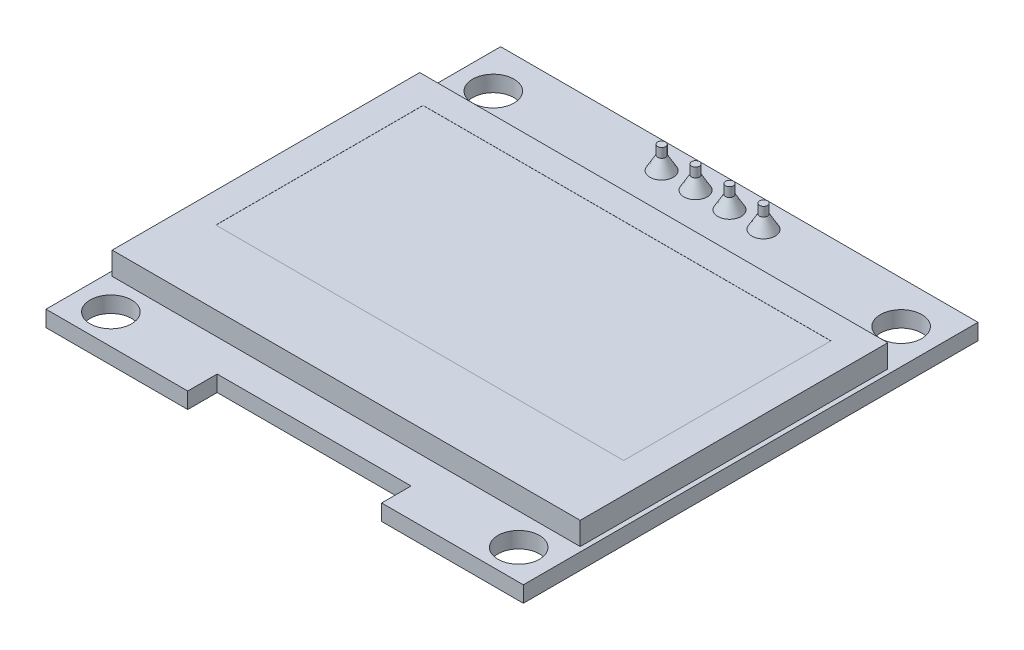
SolidWorks part; units mm, degrees
ref_plane "Ebene vorne" through (0, 0, 0) normal (0, 0, 1) x (1, 0, 0)
ref_plane "Ebene oben" through (0, 0, 0) normal (0, 1, 0) x (1, 0, 0)
ref_plane "Ebene rechts" through (0, 0, 0) normal (1, 0, 0) x (0, 0, -1)
sketch "Skizze1" plane through (0, 0, 0) normal (0, 1, 0) x (1, 0, 0)
  line L1 (-17.85, -17) -> (17.85, -17)
  line L2 (-17.85, -17) -> (-17.85, 17)
  line L3 (-17.85, 17) -> (17.85, 17)
  line L4 (17.85, -17) -> (17.85, 17)
  line L5 (-17.85, -17) -> (17.85, 17) construction
  line L6 (-17.85, 17) -> (17.85, -17) construction
  point P0 (0, 0)
  dimension "D1" = 35.7
  dimension "D2" = 34
extrude "Aufsatz-Linear austragen1" add sketch "Skizze1" along normal blind 1.2
sketch "Skizze2" plane through (0, 1.2, 0) normal (0, 1, 0) x (1, 0, 0)
  line L0 (0, 17) -> (0, -17) construction
  line L1 (17.85, 17) -> (-17.85, 17) construction
  line L2 (-17.85, -17) -> (17.85, -17) construction
  circle A0 centre (-15.25, 13.85) radius 1.55
  circle A1 centre (15.25, 13.85) radius 1.55
  circle A2 centre (15.25, -14.75) radius 1.55
  circle A3 centre (-15.25, -14.75) radius 1.55
  dimension "D4" = 3.1
  dimension "D1" = 28.6
  dimension "D2" = 30.5
  dimension "D3" = 3.15
extrude "Schnitt-Linear austragen1" cut sketch "Skizze2" against normal through all
sketch "Skizze3" plane through (0, 1.2, 0) normal (0, 1, 0) x (1, 0, 0)
  line L0 (0, 0) -> (0, 10.6) construction
  line L1 (-17.5, 10.6) -> (17.5, 10.6)
  line L2 (-17.5, 10.6) -> (-17.5, -12.4)
  line L3 (-17.5, -12.4) -> (17.5, -12.4)
  line L4 (17.5, 10.6) -> (17.5, -12.4)
  line L5 (17.85, 17) -> (-17.85, 17) construction
  dimension "D1" = 35
  dimension "D2" = 23
  dimension "D3" = 6.4
extrude "Aufsatz-Linear austragen2" add sketch "Skizze3" along normal blind 1.7
sketch "Skizze4" plane through (0, 2.9, 0) normal (0, 1, 0) x (1, 0, 0)
  line L0 (0, 0) -> (0, 8.6) construction
  line L1 (-15.25, 8.6) -> (15.25, 8.6)
  line L2 (-15.25, 8.6) -> (-15.25, -6.9)
  line L3 (-15.25, -6.9) -> (15.25, -6.9)
  line L4 (15.25, 8.6) -> (15.25, -6.9)
  line L5 (17.5, 10.6) -> (-17.5, 10.6) construction
  dimension "D1" = 30.5
  dimension "D2" = 15.5
  dimension "D3" = 2
extrude "Schnitt-Linear austragen2" cut sketch "Skizze4" against normal blind 0.01
sketch "Skizze5" plane through (0, 1.2, 0) normal (0, 1, 0) x (1, 0, 0)
  line L0 (-17.85, -17) -> (17.85, -17) construction
  line L1 (-7.25, -17) -> (7.25, -17)
  line L2 (-7.25, -17) -> (-7.25, -14.8)
  line L3 (-7.25, -14.8) -> (7.25, -14.8)
  line L4 (7.25, -17) -> (7.25, -14.8)
  line L5 (0, 0) -> (0, -14.8) construction
  dimension "D1" = 14.5
  dimension "D2" = 2.2
extrude "Schnitt-Linear austragen3" cut sketch "Skizze5" against normal through all
sketch "Skizze6" plane through (0, 1.2, 0) normal (0, 1, 0) x (1, 0, 0)
  line L0 (17.85, 17) -> (-17.85, 17) construction
  line L1 (-3.81, 15) -> (3.81, 15) construction
  line L2 (0, 0) -> (0, 15) construction
  circle A0 centre (-3.81, 15) radius 0.875
  circle A1 centre (3.81, 15) radius 0.875
  circle A2 centre (1.27, 15) radius 0.875
  circle A3 centre (-1.27, 15) radius 0.875
  dimension "D5" = 1.75
  dimension "D1" = 2.54
  dimension "D2" = 2.54
  dimension "D3" = 2.54
  dimension "D4" = 2
extrude "Aufsatz-Linear austragen3" add sketch "Skizze6" along normal blind 1 draft 30
sketch "Skizze7" plane through (0, 2.2, 0) normal (0, 1, 0) x (1, 0, 0)
  circle A0 centre (-1.27, 15) radius 0.2976 construction
  circle A1 centre (-3.81, 15) radius 0.2976
  circle A2 centre (-3.81, 15) radius 0.2976
  circle A3 centre (1.27, 15) radius 0.2976 construction
  circle A4 centre (-1.27, 15) radius 0.2976
  circle A5 centre (1.27, 15) radius 0.2976
  circle A7 centre (3.81, 15) radius 0.2976
  circle A8 centre (3.81, 15) radius 0.2976
  dimension "D1" = 0
  dimension "D2" = 0
extrude "Aufsatz-Linear austragen4" add sketch "Skizze7" along normal blind 0.7
sketch "Skizze8" plane through (0, 0, 0) normal (0, -1, 0) x (1, 0, 0)
  circle A0 centre (-3.81, -15) radius 0.2976 construction
  circle A1 centre (-1.27, -15) radius 0.2976
  circle A2 centre (-1.27, -15) radius 0.2976
  circle A3 centre (1.27, -15) radius 0.2976 construction
  circle A4 centre (3.81, -15) radius 0.2976 construction
  circle A5 centre (-3.81, -15) radius 0.2976
  circle A6 centre (1.27, -15) radius 0.2976
  circle A7 centre (3.81, -15) radius 0.2976
  dimension "D1" = 0
extrude "Aufsatz-Linear austragen5" add sketch "Skizze8" along normal blind 8.5
sketch "Skizze9" plane through (0, 0, 0) normal (0, -1, 0) x (1, 0, 0)
  line L0 (-3.81, -15) -> (-5.05, -15) construction
  line L1 (-5.05, -13.73) -> (5.05, -13.73)
  line L2 (-5.05, -13.73) -> (-5.05, -16.27)
  line L3 (-5.05, -16.27) -> (5.05, -16.27)
  line L4 (5.05, -13.73) -> (5.05, -16.27)
  line L5 (-3.81, -15) -> (3.81, -15) construction
  line L6 (0, -15) -> (0, -13.73) construction
  dimension "D1" = 2.54
  dimension "10.1" = 10.1
extrude "Aufsatz-Linear austragen6" add sketch "Skizze9" along normal blind 1.8 separate body
equation "\"D1@Skizze2\"=31.7-3.1"
equation "\"D2@Skizze2\"=33.6-3.1"
equation "\"D3@Skizze2\"=1.6+1.55"
equation "\"D2@Skizze6\"=\"D1@Skizze6\""
equation "\"D3@Skizze6\"=\"D1@Skizze6\""
